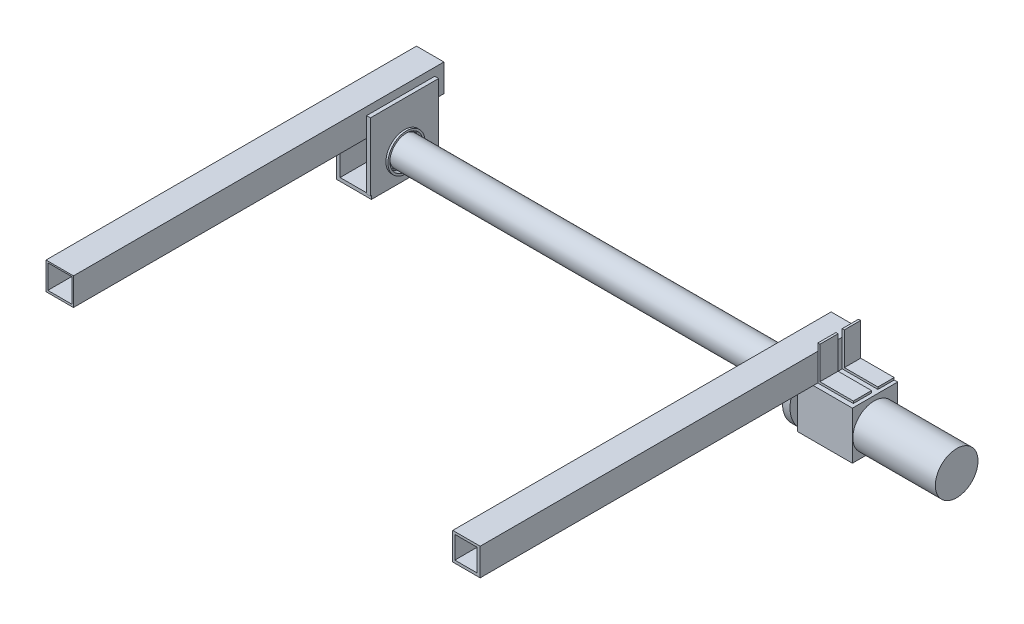
SolidWorks part; units mm, degrees
ref_plane "前视基准面" through (0, 0, 0) normal (0, 0, 1) x (1, 0, 0)
ref_plane "上视基准面" through (0, 0, 0) normal (0, 1, 0) x (1, 0, 0)
ref_plane "右视基准面" through (0, 0, 0) normal (1, 0, 0) x (0, 0, -1)
sketch "草图1" plane through (0, 0, 0) normal (0, 0, 1) x (1, 0, 0)
  line L1 (-14.5852, -12.3753) -> (10.9848, -12.3753)
  line L2 (-14.5852, -12.3753) -> (-14.5852, 13.1947)
  line L3 (-14.5852, 13.1947) -> (10.9848, 13.1947)
  line L4 (10.9848, -12.3753) -> (10.9848, 13.1947)
extrude "凸台-拉伸1" add sketch "草图1" along normal blind 345
sketch "草图2" plane through (0, 0, 345) normal (0, 0, 1) x (1, 0, 0)
  line L1 (-12.8695, -10.4334) -> (9.4005, -10.4334)
  line L2 (-12.8695, -10.4334) -> (-12.8695, 11.8366)
  line L3 (-12.8695, 11.8366) -> (9.4005, 11.8366)
  line L4 (9.4005, -10.4334) -> (9.4005, 11.8366)
extrude "切除-拉伸1" cut sketch "草图2" against normal blind 345
sketch "草图3" plane through (-14.5852, 0, 0) normal (-1, 0, 0) x (0, 0, 1)
  line L1 (8.5474, -57.222) -> (71.1174, -57.222)
  line L2 (8.5474, -57.222) -> (8.5474, 7.598)
  line L3 (8.5474, 7.598) -> (71.1174, 7.598)
  line L4 (71.1174, -57.222) -> (71.1174, 7.598)
extrude "凸台-拉伸2" add sketch "草图3" along normal blind 3.58
sketch "草图4" plane through (10.9848, 0, 0) normal (1, 0, 0) x (0, 0, -1)
  line L1 (-72.0874, 5.928) -> (-8.5474, 5.928)
  line L2 (-72.0874, 5.928) -> (-72.0874, -57.222)
  line L3 (-72.0874, -57.222) -> (-8.5474, -57.222)
  line L4 (-8.5474, 5.928) -> (-8.5474, -57.222)
extrude "凸台-拉伸3" add sketch "草图4" along normal blind 3.58
sketch "草图6" plane through (0, -57.222, 0) normal (0, -1, 0) x (1, 0, 0)
  line L1 (14.5648, 8.5474) -> (-18.1652, 8.5474)
  line L2 (14.5648, 8.5474) -> (14.5648, 71.1174)
  line L3 (14.5648, 71.1174) -> (-18.1652, 71.1174)
  line L4 (-18.1652, 8.5474) -> (-18.1652, 71.1174)
extrude "凸台-拉伸4" add sketch "草图6" along normal blind 3.15
sketch "草图7" plane through (14.5648, 0, 0) normal (1, 0, 0) x (0, 0, -1)
  circle A0 centre (-40.298, -36.3517) radius 14.595
extrude "切除-拉伸3" cut sketch "草图7" against normal blind 3.32
sketch "草图8" plane through (14.5648, 0, 0) normal (1, 0, 0) x (0, 0, -1)
  circle A0 centre (-40.298, -36.7158) radius 17.2665
extrude "凸台-拉伸5" add sketch "草图8" along normal blind 1.86
sketch "草图9" plane through (16.4248, 0, 0) normal (1, 0, 0) x (0, 0, -1)
  circle A0 centre (-40.298, -36.7158) radius 15.5
extrude "切除-拉伸5" cut sketch "草图9" against normal blind 5
sketch "草图10" plane through (14.5648, 0, 0) normal (1, 0, 0) x (0, 0, -1)
  circle A0 centre (-40.298, -36.3517) radius 13.5938
extrude "凸台-拉伸6" add sketch "草图10" along normal blind 380 separate body
sketch "草图11" plane through (10.9848, 0, 0) normal (-1, 0, 0) x (0, 0, 1)
  circle A0 centre (37.3604, -38.3156) radius 12.3391
extrude "凸台-拉伸7" add sketch "草图11" along normal blind 18
sketch "草图12" plane through (-7.0152, 0, 0) normal (-1, 0, 0) x (0, 0, 1)
  circle A0 centre (33.524, -38.3156) radius 16.1755
extrude "凸台-拉伸8" add sketch "草图12" along normal blind 1.5
sketch "草图13" plane through (394.5648, 0, 0) normal (1, 0, 0) x (0, 0, -1)
  circle A0 centre (-40.298, -36.3517) radius 28
extrude "凸台-拉伸9" add sketch "草图13" along normal blind 7
sketch "草图14" plane through (401.5648, 0, 0) normal (1, 0, 0) x (0, 0, -1)
  circle A0 centre (-40.298, -36.3517) radius 7.6
extrude "凸台-拉伸10" add sketch "草图14" along normal blind 15.2
sketch "草图15" plane through (401.5648, 0, 0) normal (1, 0, 0) x (0, 0, -1)
  line L1 (-61.433, -58.8247) -> (-19.2646, -58.8247)
  line L2 (-61.433, -58.8247) -> (-61.433, -14.3569)
  line L3 (-61.433, -14.3569) -> (-19.2646, -14.3569)
  line L4 (-19.2646, -58.8247) -> (-19.2646, -14.3569)
  point P4 (-58.6483, -54.0509)
extrude "凸台-拉伸11" add sketch "草图15" along normal blind 51.24
sketch "草图16" plane through (452.8048, 0, 0) normal (1, 0, 0) x (0, 0, -1)
  circle A0 centre (-41.1444, -38.5361) radius 19.865
extrude "凸台-拉伸12" add sketch "草图16" along normal blind 76.83
sketch "草图17" plane through (0, -14.3569, 0) normal (0, 1, 0) x (1, 0, 0)
  line L0 (452.8048, -19.2646) -> (401.5648, -19.2646) construction
  line L1 (416.3974, -19.2646) -> (390.8474, -19.2646)
  line L2 (416.3974, -19.2646) -> (416.3974, -371.6646)
  line L3 (416.3974, -371.6646) -> (390.8474, -371.6646)
  line L4 (390.8474, -19.2646) -> (390.8474, -371.6646)
extrude "凸台-拉伸14" add sketch "草图17" along normal blind 25.55
sketch "草图19" plane through (0, 0, 371.6646) normal (0, 0, 1) x (1, 0, 0)
  line L1 (392.8186, 8.9657) -> (413.6002, 8.9657)
  line L2 (392.8186, 8.9657) -> (392.8186, -11.816)
  line L3 (392.8186, -11.816) -> (413.6002, -11.816)
  line L4 (413.6002, 8.9657) -> (413.6002, -11.816)
extrude "切除-拉伸6" cut sketch "草图19" against normal blind 358
sketch "草图20" plane through (416.3974, 0, 0) normal (1, 0, 0) x (0, 0, -1)
  line L0 (-61.433, -14.3569) -> (-19.2646, -14.3569) construction
  line L2 (-57.2609, -14.3569) -> (-40.3488, -14.3569)
  line L3 (-57.2609, -14.3569) -> (-57.2609, 17.8879)
  line L4 (-57.2609, 17.8879) -> (-40.3488, 17.8879)
  line L5 (-40.3488, -14.3569) -> (-40.3488, 17.8879)
extrude "凸台-拉伸15" add sketch "草图20" along normal blind 2
sketch "草图21" plane through (416.3974, 0, 0) normal (1, 0, 0) x (0, 0, -1)
  line L1 (-19.2646, -14.3569) -> (-34.4877, -14.3569)
  line L2 (-19.2646, -14.3569) -> (-19.2646, 18.1051)
  line L3 (-19.2646, 18.1051) -> (-34.4877, 18.1051)
  line L4 (-34.4877, -14.3569) -> (-34.4877, 18.1051)
extrude "凸台-拉伸16" add sketch "草图21" along normal blind 2
sketch "草图22" plane through (0, -14.3569, 0) normal (0, 1, 0) x (1, 0, 0)
  line L0 (418.3974, -57.2609) -> (418.3974, -40.3488) construction
  line L1 (418.3974, -57.2609) -> (449.5288, -57.2609)
  line L2 (418.3974, -57.2609) -> (418.3974, -40.3488)
  line L3 (418.3974, -40.3488) -> (449.5288, -40.3488)
  line L4 (449.5288, -57.2609) -> (449.5288, -40.3488)
extrude "凸台-拉伸17" add sketch "草图22" along normal blind 2
sketch "草图23" plane through (0, -14.3569, 0) normal (0, 1, 0) x (1, 0, 0)
  line L0 (452.8048, -19.2646) -> (418.3974, -19.2646) construction
  line L1 (418.3974, -34.4877) -> (449.5996, -34.4877)
  line L2 (418.3974, -34.4877) -> (418.3974, -19.2646)
  line L3 (418.3974, -19.2646) -> (449.5996, -19.2646)
  line L4 (449.5996, -34.4877) -> (449.5996, -19.2646)
extrude "凸台-拉伸18" add sketch "草图23" along normal blind 2
equation "\"345.82.mm\"=10"
